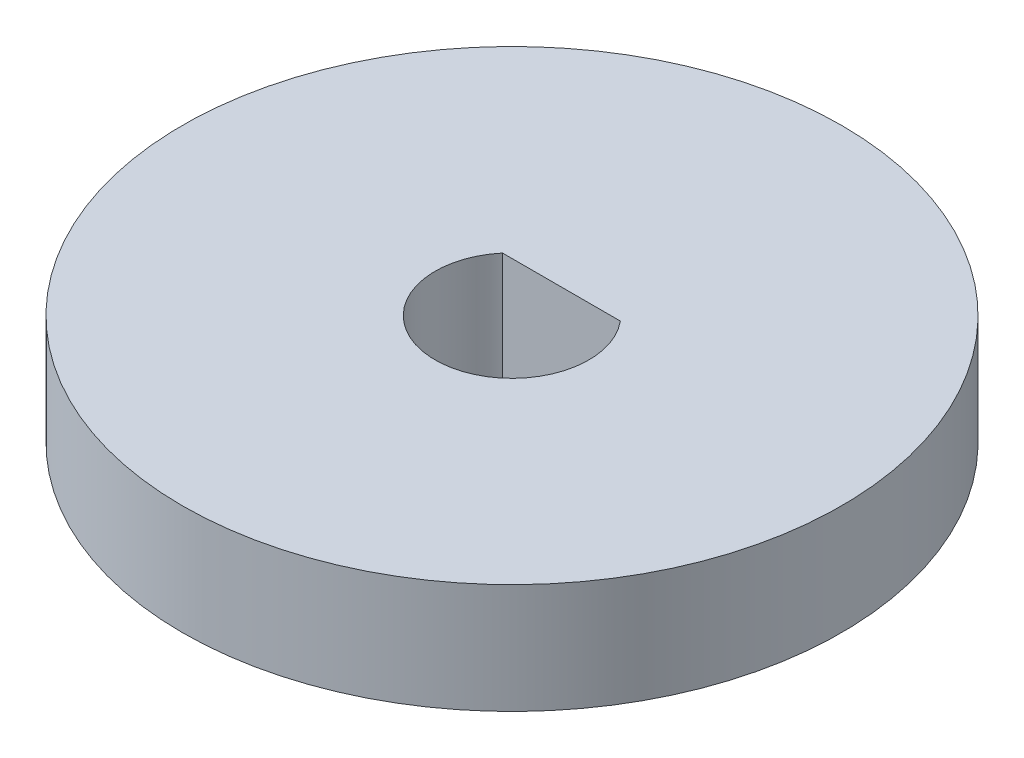
SolidWorks part; units mm, degrees
ref_plane "Спереди" through (0, 0, 0) normal (0, 0, 1) x (1, 0, 0)
ref_plane "Сверху" through (0, 0, 0) normal (0, 1, 0) x (1, 0, 0)
ref_plane "Справа" through (0, 0, 0) normal (1, 0, 0) x (0, 0, -1)
sketch "Эскиз1" plane through (0, 0, 0) normal (0, 1, 0) x (1, 0, 0)
  line L0 (-1.0724, 0.9) -> (1.0724, 0.9)
  arc A3 (-1.0724, 0.9) -> (1.0724, 0.9) centre (0, 0) ccw
  circle A4 centre (0, 0) radius 6
  point P1 (0, -1.4)
  dimension "D1" = 2.8
  dimension "D2" = 2.3
extrude "Бобышка-Вытянуть1" add sketch "Эскиз1" along normal blind 2
